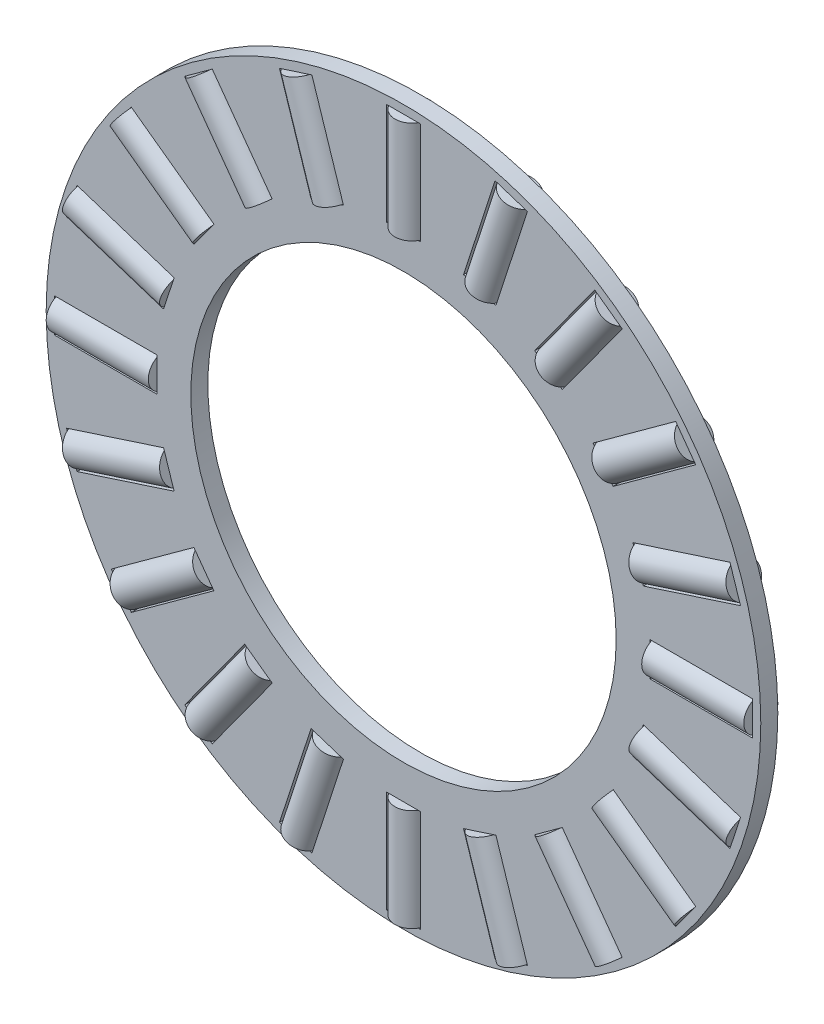
SolidWorks part; units mm, degrees
ref_plane "前视基准面" through (0, 0, 0) normal (0, 0, 1) x (1, 0, 0)
ref_plane "上视基准面" through (0, 0, 0) normal (0, 1, 0) x (1, 0, 0)
ref_plane "右视基准面" through (0, 0, 0) normal (1, 0, 0) x (0, 0, -1)
other "Configuration Table"
sketch "草图1" plane through (0, 0, 0) normal (0, 0, 1) x (1, 0, 0)
  circle A0 centre (0, 0) radius 21
  circle A1 centre (0, 0) radius 12.5
  dimension "D1" = 25
  dimension "D2" = 42
extrude "凸台-拉伸1" add sketch "草图1" along normal blind 1 contours A0 | A1
ref_plane "基准面1" through (0, 0, 0.5) normal (0, 0, 1) x (1, 0, 0)
sketch "草图3" plane through (0, 0, 0.5) normal (0, 0, 1) x (1, 0, 0)
  line L0 (0, 14.5) -> (1, 14.5)
  line L1 (0, -0.55) -> (0, 0.55) construction
  line L2 (1, 14.5) -> (1, 20.5)
  line L3 (1, 20.5) -> (-1, 20.5)
  line L4 (-1, 20.5) -> (-1, 14.5)
  line L5 (-1, 14.5) -> (0, 14.5)
  line L6 (0.55, 0) -> (-0.55, 0) construction
  line L7 (0, 21.9842) -> (0, 13.7018) construction
  dimension "D1" = 2
  dimension "D2" = 6
  dimension "D3" = 1
  dimension "D4" = 14.5
extrude "切除-拉伸1" cut sketch "草图3" against normal through all and the other way through all
pattern_circular "阵列(圆周)1" count 20 over 360 about axis through (0, 0, 0) along (0, 0, 1) of "切除-拉伸1"
ref_plane "基准面2" through (0, 20.5, 0) normal (0, 1, 0) x (1, 0, 0)
sketch "草图5" plane through (0, 20.5, 0) normal (0, 1, 0) x (1, 0, 0)
  line L0 (-23.1, -0.5) -> (23.1, -0.5) construction
  line L1 (0, -0.55) -> (0, 0.55) construction
  circle A0 centre (0, -0.5) radius 1
  dimension "D1" = 2
extrude "凸台-拉伸5" add sketch "草图5" against normal up to surface (6 mm away) separate body up to face at (0, 14.5, 0.5)
pattern_circular "阵列(圆周)8" count 20 over 360 about axis through (0, 0, 0) along (0, 0, 1) of bodies 110
